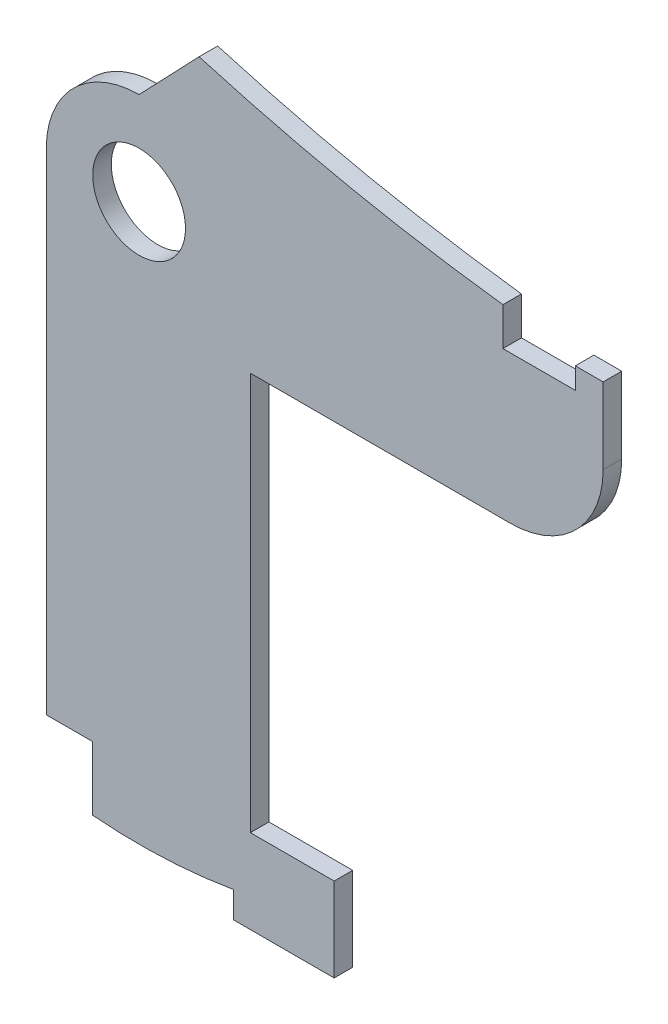
SolidWorks part; units mm, degrees
ref_plane "정면" through (0, 0, 0) normal (0, 0, 1) x (1, 0, 0)
ref_plane "윗면" through (0, 0, 0) normal (0, 1, 0) x (1, 0, 0)
ref_plane "우측면" through (0, 0, 0) normal (1, 0, 0) x (0, 0, -1)
sketch "스케치1" plane through (0, 0, 0) normal (0, 0, 1) x (1, 0, 0)
  line L1 (17.6552, -8.2873) -> (20.8871, -4.904)
  line L15 (37.2552, -8.2873) -> (37.2552, -10.3366)
  line L16 (37.2552, -10.3366) -> (41.1552, -10.3366)
  line L20 (41.1552, -10.3366) -> (41.1552, -9.1914)
  line L21 (41.1552, -9.1914) -> (42.6552, -9.1914)
  line L22 (42.6552, -9.1914) -> (42.6552, -13.2873)
  line L23 (37.6552, -18.2873) -> (23.65, -18.2873)
  line L24 (23.65, -18.2873) -> (23.65, -39.725)
  line L25 (22.7313, -44.2491) -> (28.1634, -44.2491)
  line L26 (12.6552, -39.725) -> (12.6552, -13.2873)
  line L27 (28.1634, -44.2491) -> (28.1634, -39.725)
  line L28 (28.1634, -39.725) -> (23.65, -39.725)
  line L29 (23.65, -39.725) -> (25.9067, -39.725)
  line L33 (15.1552, -43.1618) -> (15.1552, -39.725)
  line L34 (15.1552, -39.725) -> (12.6552, -39.725)
  line L35 (22.7313, -42.8333) -> (22.7313, -44.2491)
  circle A3 centre (17.6552, -13.2873) radius 2.5
  arc A6 (17.6552, -8.2873) -> (12.6552, -13.2873) centre (17.6552, -13.2873) ccw
  arc A7 (15.1552, -43.1618) -> (22.7313, -42.8333) centre (17.6552, -13.2873) ccw
  arc A9 (37.2552, -8.2873) -> (20.8871, -4.904) centre (49.9016, 94.181) cw
  arc A10 (42.6552, -13.2873) -> (37.6552, -18.2873) centre (37.6552, -13.2873) cw
  dimension "D1" = 19.6
  dimension "D2" = 1.5
  dimension "D5" = 5
  dimension "D6" = 5
  dimension "D7" = 30
extrude "보스-돌출1" add sketch "스케치1" along normal blind 1
